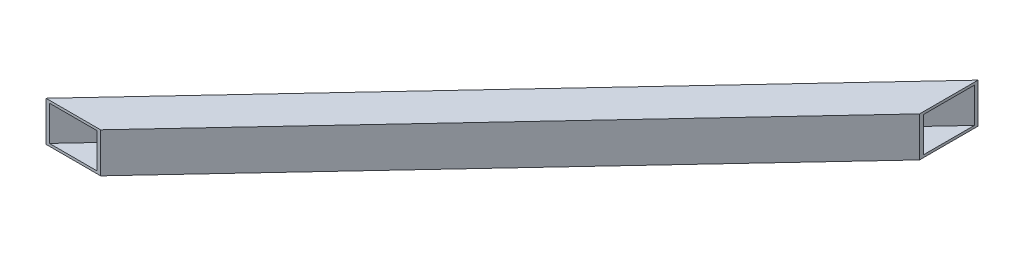
SolidWorks part; units mm, degrees
ref_plane "Front Plane" through (0, 0, 0) normal (0, 0, 1) x (1, 0, 0)
ref_plane "Top Plane" through (0, 0, 0) normal (0, 1, 0) x (1, 0, 0)
ref_plane "Right Plane" through (0, 0, 0) normal (1, 0, 0) x (0, 0, -1)
sketch "Sketch1" plane through (0, 0, 0) normal (0, 1, 0) x (1, 0, 0)
  line L0 (-114.0193, -108.0259) -> (-87.9422, -108.0259)
  line L1 (-87.9422, -108.0259) -> (100.9807, 94.0777)
  line L2 (100.9807, 94.0777) -> (100.9807, 121.9741)
  line L3 (100.9807, 121.9741) -> (-114.0193, -108.0259)
  line L4 (-6.5193, 6.9741) -> (6.5193, -6.9741) construction
  point P7 (-6.5193, 6.9741)
  point P9 (6.5193, -6.9741)
  point P10 (0, 0)
  dimension "D1" = 19.05
  dimension "D2" = 230
  dimension "D3" = 215
sketch "Sketch4" plane through (0, 0, 0) normal (0, 1, 0) x (1, 0, 0)
  line L10 (99.7807, 94.5512) -> (99.7807, 118.9331)
  line L11 (-88.4631, -106.8259) -> (99.7807, 94.5512)
  line L12 (-111.2549, -106.8259) -> (-88.4631, -106.8259)
  line L13 (99.7807, 118.9331) -> (-111.2549, -106.8259)
  line L14 (100.9807, 95.835) -> (100.9807, 120.2168)
  line L15 (-89.5848, -108.0259) -> (100.9807, 95.835)
  line L16 (-112.3766, -108.0259) -> (-89.5848, -108.0259)
  line L17 (100.9807, 120.2168) -> (-112.3766, -108.0259)
  line L18 (-114.0193, -108.0259) -> (-87.9422, -108.0259) construction
  line L19 (100.9807, 94.0777) -> (100.9807, 121.9741) construction
  dimension "D1" = 1.2
extrude "Boss-Extrude2" add sketch "Sketch1" along normal mid plane 19.05
extrude "Cut-Extrude1" cut sketch "Sketch4" against normal mid plane 16.65
